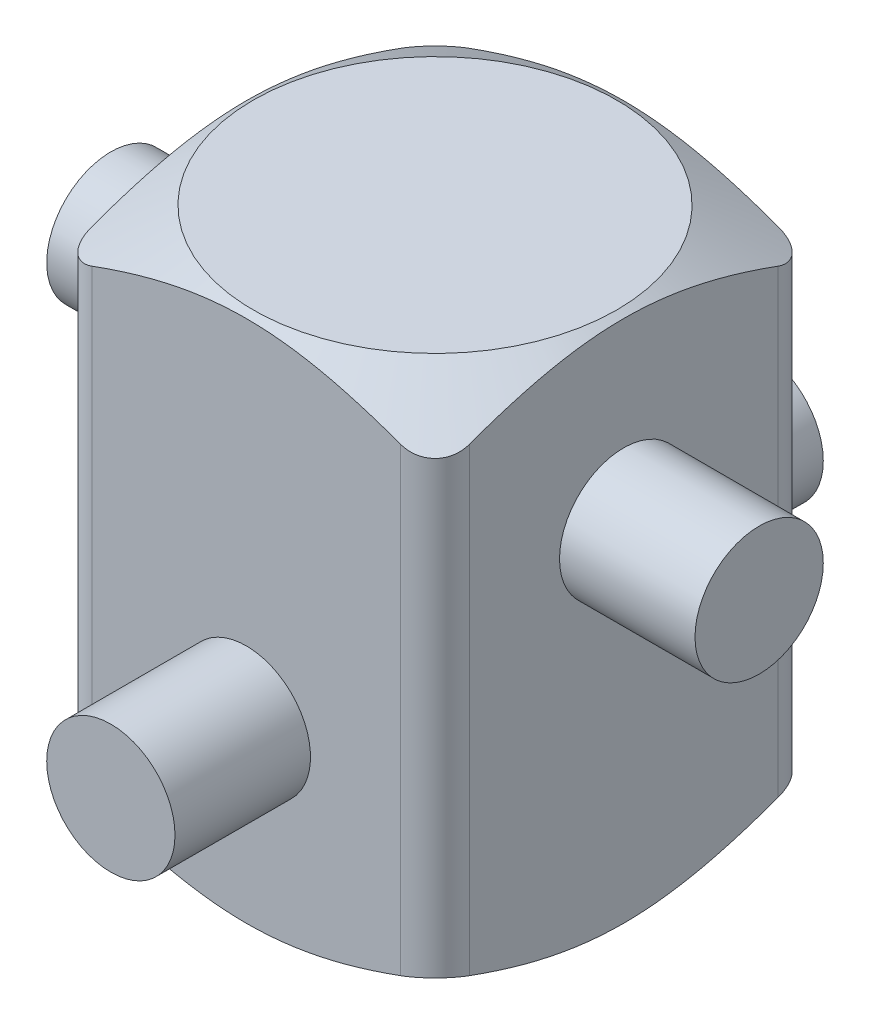
SolidWorks part; units mm, degrees
material "AISI Type A2 Tool Steel"
ref_plane "FRONT" through (0, 0, 0) normal (0, 0, 1) x (1, 0, 0)
ref_plane "TOP" through (0, 0, 0) normal (0, 1, 0) x (1, 0, 0)
ref_plane "SIDE" through (0, 0, 0) normal (1, 0, 0) x (0, 0, -1)
sketch "Intermediate_Body-Sk" plane through (0, 0, 0) normal (0, 1, 0) x (1, 0, 0)
  line L1 (-6.985, -6.985) -> (6.985, -6.985)
  line L2 (-6.985, -6.985) -> (-6.985, 6.985)
  line L3 (-6.985, 6.985) -> (6.985, 6.985)
  line L4 (6.985, -6.985) -> (6.985, 6.985)
  line L5 (-6.985, -6.985) -> (6.985, 6.985) construction
  line L6 (-6.985, 6.985) -> (6.985, -6.985) construction
  point P0 (0, 0)
  dimension "DimA" = 13.97
extrude "Intermediate_Body" add sketch "Intermediate_Body-Sk" along normal blind 19.685
sketch "Rev-CutSk" plane through (0, 0, 0) normal (0, 0, 1) x (1, 0, 0)
  line L0 (-6.731, 19.685) -> (-13.081, 16.0188)
  line L1 (-6.985, 19.685) -> (6.985, 19.685) construction
  line L2 (-13.081, 16.0188) -> (-13.081, 3.6662)
  line L3 (-13.081, 3.6662) -> (-6.731, 0)
  line L4 (7.1247, 0) -> (-7.1247, 0) construction
  line L5 (-6.731, 0) -> (-6.731, 19.685) construction
  line L6 (-6.985, 19.685) -> (-6.985, 0) construction
  line L7 (-6.731, 19.685) -> (-15.621, 19.685)
  line L8 (-15.621, 19.685) -> (-15.621, 0)
  line L9 (-15.621, 0) -> (-6.731, 0)
  line L10 (0, 0) -> (0, 19.685) construction
  dimension "D1" = 30
  dimension "D2" = 0.254
  dimension "D3" = 6.35
  dimension "D4" = 2.54
revolve "Cut-Revolve2" cut sketch "Rev-CutSk" angle 360 about L10
sketch "Pin1" plane through (0, 0, 0) normal (0, 0, 1) x (1, 0, 0)
  line L0 (0, -6.2865) -> (0, 6.2865) construction
  line L1 (7.1247, 0) -> (-7.1247, 0) construction
  circle A0 centre (0, 6.6675) radius 2.3749
  dimension "Pin_Dia" = 4.7498
  dimension "Pin_Dist" = 6.6675
extrude "Pin-Extrude1" add sketch "Pin1" along normal mid plane 24.003
sketch "Pin2" plane through (0, 0, 0) normal (1, 0, 0) x (0, 0, -1)
  line L0 (0, 6.2865) -> (0, -6.2865) construction
  line L1 (6.731, 19.685) -> (-6.731, 19.685) construction
  circle A0 centre (0, 13.0175) radius 2.3749
  dimension "D1" = 4.7498
  dimension "D2" = 6.6675
extrude "Pin-Extrude2" add sketch "Pin2" along normal mid plane 24.003
fillet "Fillet1" radius 1.27 4 edges at (6.985, 9.8425, -6.985) (-6.985, 9.8425, -6.985) (-6.985, 9.8425, 6.985) (6.985, 9.8425, 6.985)
equation "\"D1@Pin2\"=\"Pin_Dia@Pin1\""
equation "\"D2@Pin2\"=\"Pin_Dist@Pin1\""
equation "\"D1@Pin-Extrude2\"=\"UDIA@Pin-Extrude1\""
